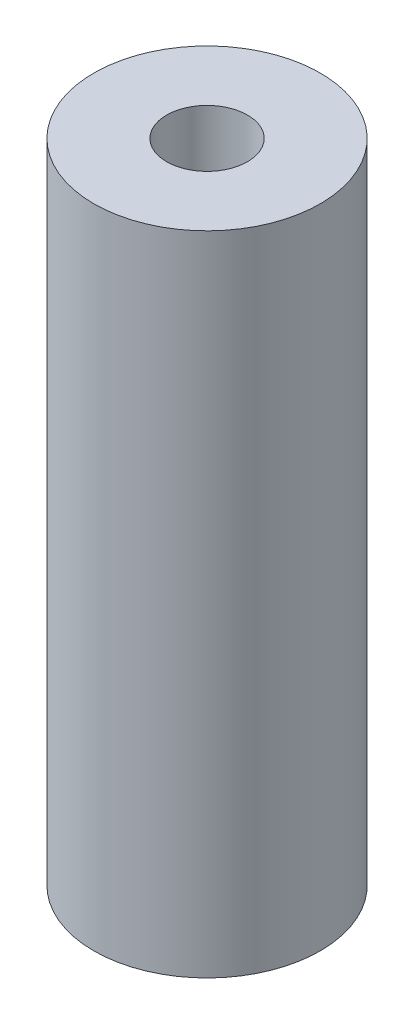
SolidWorks part; units mm, degrees
ref_plane "Спереди" through (0, 0, 0) normal (0, 0, 1) x (1, 0, 0)
ref_plane "Сверху" through (0, 0, 0) normal (0, 1, 0) x (1, 0, 0)
ref_plane "Справа" through (0, 0, 0) normal (1, 0, 0) x (0, 0, -1)
sketch "Эскиз1" plane through (0, 0, 0) normal (0, 1, 0) x (1, 0, 0)
  circle A0 centre (0, 0) radius 7
  circle A1 centre (0, 0) radius 2.5
extrude "Вытянуть1" add sketch "Эскиз1" along normal blind 40
